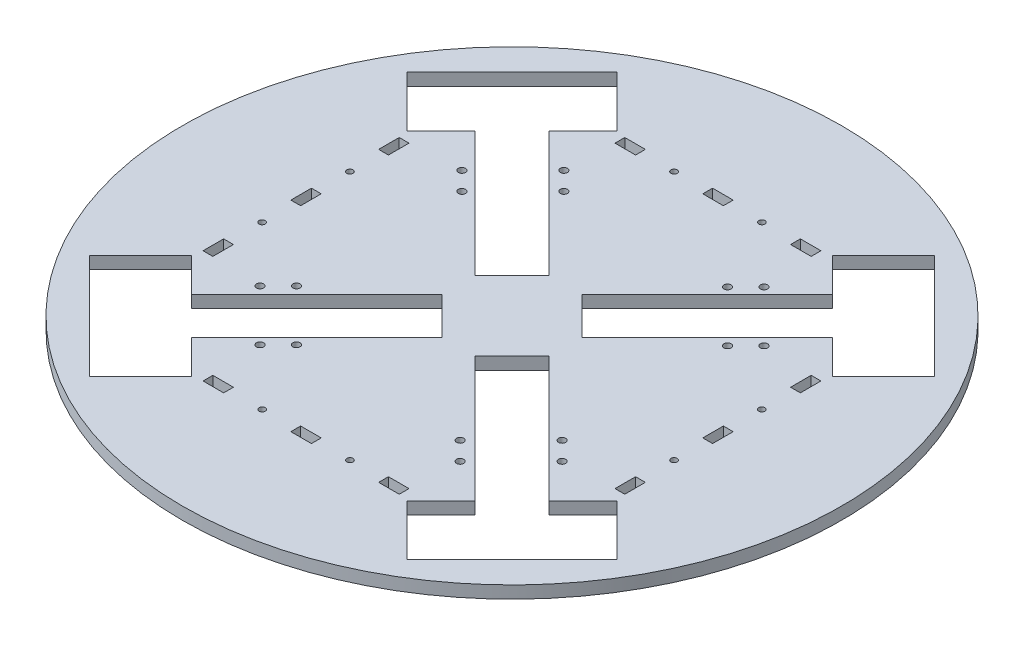
SolidWorks part; units mm, degrees
ref_plane "Front Plane" through (0, 0, 0) normal (0, 0, 1) x (1, 0, 0)
ref_plane "Top Plane" through (0, 0, 0) normal (0, 1, 0) x (1, 0, 0)
ref_plane "Right Plane" through (0, 0, 0) normal (1, 0, 0) x (0, 0, -1)
sketch "Sketch1" plane through (0, 0, 0) normal (0, 1, 0) x (1, 0, 0)
  line L1 (0, 0) -> (-200, 0) construction
  line L2 (0, 0) -> (0, 200) construction
  line L3 (0, 200) -> (-200, 200) construction
  line L4 (-200, 0) -> (-200, 200) construction
  circle A0 centre (-100, 100) radius 160
  point P8 (-100, 200)
  point P9 (-200, 100)
  dimension "D3" = 320
  dimension "D1" = 200
  dimension "D2" = 200
extrude "Boss-Extrude1" add sketch "Sketch1" along normal blind 6 contours A0
sketch "Sketch2" plane through (0, 6, 0) normal (0, 1, 0) x (1, 0, 0)
  line L0 (-260, 100) -> (60, 100) construction
  line L1 (-213.1371, -13.1371) -> (-100, 100) construction
  line L2 (-100, 100) -> (13.1371, 213.1371) construction
  line L3 (-213.1371, 213.1371) -> (13.1371, -13.1371) construction
  circle A0 centre (-100, 100) radius 160 construction
  dimension "D1" = 45
  dimension "D2" = 45
sketch "Sketch3" plane through (0, 0, 0) normal (0, -1, 0) x (1, 0, 0)
  line L0 (-22.9254, -227.9863) -> (-47.6741, -203.2376)
  line L1 (-22.9254, -227.9863) -> (27.9863, -177.0746)
  line L2 (-47.6741, -203.2376) -> (3.2376, -152.3259)
  line L3 (27.9863, -177.0746) -> (3.2376, -152.3259)
  line L4 (3.2376, -47.6741) -> (27.9863, -22.9254)
  line L5 (3.2376, -47.6741) -> (-47.6741, 3.2376)
  line L6 (27.9863, -22.9254) -> (-22.9254, 27.9863)
  line L7 (-47.6741, 3.2376) -> (-22.9254, 27.9863)
  line L8 (-152.3259, 3.2376) -> (-177.0746, 27.9863)
  line L9 (-152.3259, 3.2376) -> (-203.2376, -47.6741)
  line L10 (-177.0746, 27.9863) -> (-227.9863, -22.9254)
  line L11 (-203.2376, -47.6741) -> (-227.9863, -22.9254)
  line L12 (-177.0746, -227.9863) -> (-152.3259, -203.2376)
  line L13 (-177.0746, -227.9863) -> (-227.9863, -177.0746)
  line L14 (-152.3259, -203.2376) -> (-203.2376, -152.3259)
  line L15 (-227.9863, -177.0746) -> (-203.2376, -152.3259)
  line L16 (-213.1371, -213.1371) -> (13.1371, 13.1371) construction
  line L17 (-100, -100) -> (13.1371, -213.1371) construction
  line L18 (-213.1371, 13.1371) -> (-100, -100) construction
  point P26 (2.5305, -202.5305)
  point P27 (2.5305, 2.5305)
  point P28 (-202.5305, 2.5305)
  point P29 (-202.5305, -202.5305)
  dimension "D1" = 35
  dimension "D2" = 15
  dimension "D3" = 15
  dimension "D4" = 15
  dimension "D5" = 15
  dimension "D6" = 72
extrude "Cut-Extrude1" cut sketch "Sketch3" against normal through all
sketch "Sketch4" plane through (0, 0, 0) normal (0, -1, 0) x (1, 0, 0)
  line L0 (-13.2026, -31.2339) -> (-31.2339, -13.2026)
  line L1 (-13.2026, -31.2339) -> (-74.0138, -92.045)
  line L2 (-31.2339, -13.2026) -> (-92.045, -74.0138)
  line L3 (-74.0138, -92.045) -> (-92.045, -74.0138)
  line L4 (-168.7661, -13.2026) -> (-186.7974, -31.2339)
  line L5 (-168.7661, -13.2026) -> (-107.955, -74.0138)
  line L6 (-186.7974, -31.2339) -> (-125.9862, -92.045)
  line L7 (-107.955, -74.0138) -> (-125.9862, -92.045)
  line L8 (-203.2376, -47.6741) -> (-152.3259, 3.2376) construction
  line L9 (-186.7974, -168.7661) -> (-125.9862, -107.955)
  line L10 (-186.7974, -168.7661) -> (-168.7661, -186.7974)
  line L11 (-125.9862, -107.955) -> (-107.955, -125.9862)
  line L12 (-168.7661, -186.7974) -> (-107.955, -125.9862)
  line L13 (-13.2026, -168.7661) -> (-31.2339, -186.7974)
  line L14 (-13.2026, -168.7661) -> (-74.0138, -107.955)
  line L15 (-31.2339, -186.7974) -> (-92.045, -125.9862)
  line L16 (-74.0138, -107.955) -> (-92.045, -125.9862)
  line L17 (-100, -100) -> (13.1371, -213.1371) construction
  line L18 (-213.1371, -213.1371) -> (13.1371, 13.1371) construction
  line L19 (-213.1371, 13.1371) -> (-100, -100) construction
  line L20 (-47.6741, 3.2376) -> (3.2376, -47.6741) construction
  line L21 (-152.3259, -203.2376) -> (-203.2376, -152.3259) construction
  line L22 (3.2376, -152.3259) -> (-47.6741, -203.2376) construction
  point P22 (-83.0294, -116.9706)
  point P23 (-116.9706, -83.0294)
  point P26 (-83.0294, -83.0294)
  point P27 (-116.9706, -116.9706)
  point P35 (-100, -100)
  point P36 (-100, -100)
  line M20 (-203.2376, -152.3259) -> (-152.3259, -203.2376)
  line M22 (-152.3259, 3.2376) -> (-203.2376, -47.6741)
  line M26 (3.2376, -47.6741) -> (-47.6741, 3.2376)
  line M32 (-47.6741, -203.2376) -> (3.2376, -152.3259)
  dimension "D1" = 25.5
  dimension "D2" = 86
extrude "Cut-Extrude2" cut sketch "Sketch4" against normal through all contours L14 L16 L15 M32 | L12 L11 L9 M20 | L7 L5 L6 M22 | L3 L1 L2 M26
sketch "Sketch7" plane through (0, 0, 0) normal (0, -1, 0) x (1, 0, 0)
  line L0 (-152.3259, -203.2376) -> (-168.7661, -186.7974) construction
  line L1 (-168.7661, -186.7974) -> (-107.955, -125.9862) construction
  line L2 (-152.3259, -203.2376) -> (-168.7661, -186.7974) construction
  line L3 (-168.7661, -186.7974) -> (-107.955, -125.9862) construction
  circle A2 centre (-149.0025, -26.673) radius 1.75
  circle A10 centre (-148.5782, -173.7512) radius 1.75
  circle A20 centre (-140.1637, -35.5119) radius 1.75
  circle A21 centre (-164.9124, -60.2606) radius 1.75
  circle A22 centre (-173.7512, -51.4218) radius 1.75
  circle A25 centre (-173.327, -149.0025) radius 1.75
  circle A26 centre (-164.4881, -140.1637) radius 1.75
  circle A27 centre (-139.7394, -164.9124) radius 1.75
  circle A32 centre (-26.673, -50.9975) radius 1.75
  circle A33 centre (-35.5119, -59.8363) radius 1.75
  circle A34 centre (-60.2606, -35.0876) radius 1.75
  circle A35 centre (-51.4218, -26.2488) radius 1.75
  circle A36 centre (-50.9975, -173.327) radius 1.75
  circle A37 centre (-59.8363, -164.4881) radius 1.75
  circle A38 centre (-35.0876, -139.7394) radius 1.75
  circle A39 centre (-26.2488, -148.5782) radius 1.75
  point P29 (-100, -100)
  dimension "D9" = 3.5
  dimension "D1" = 12.5
  dimension "D2" = 35
  dimension "D3" = 35
  dimension "D4" = 12.5
  dimension "D5" = 37.1652
  dimension "D6" = 23.5
  dimension "D7" = 5.05
  dimension "D8" = 29.95
  dimension "D10" = 4
extrude "Cut-Extrude3" cut sketch "Sketch7" against normal through all
sketch "Sketch8" plane through (0, 6, 0) normal (0, 1, 0) x (1, 0, 0)
  line L1 (0, 200) -> (-200, 200) construction
  line L2 (0, 200) -> (0, 0) construction
  line L3 (0, 0) -> (-200, 0) construction
  line L4 (-200, 200) -> (-200, 0) construction
  line L5 (0, 200) -> (-200, 0) construction
  line L6 (0, 0) -> (-200, 200) construction
  point P0 (-100, 100)
  dimension "D1" = 200
  dimension "D2" = 200
sketch "Sketch9" plane through (0, 0, 0) normal (0, -1, 0) x (1, 0, 0)
  line L0 (-2.375, -119.8125) -> (-2.375, -122.8125) construction
  line L1 (-2.375, -122.8125) -> (2.375, -122.8125) construction
  line L2 (2.375, -122.8125) -> (2.375, -119.8125) construction
  line L3 (2.375, -119.8125) -> (-2.375, -119.8125) construction
  line L4 (-2.375, -77.1875) -> (-2.375, -80.1875) construction
  line L5 (-2.375, -80.1875) -> (2.375, -80.1875) construction
  line L6 (2.375, -80.1875) -> (2.375, -77.1875) construction
  line L7 (2.375, -77.1875) -> (-2.375, -77.1875) construction
  line L8 (2.375, -147.625) -> (2.375, -137.625) construction
  line L9 (2.375, -137.625) -> (-2.375, -137.625) construction
  line L10 (-2.375, -137.625) -> (-2.375, -147.625) construction
  line L11 (-2.375, -147.625) -> (2.375, -147.625) construction
  line L12 (2.375, -105) -> (2.375, -95) construction
  line L13 (2.375, -95) -> (-2.375, -95) construction
  line L14 (-2.375, -95) -> (-2.375, -105) construction
  line L15 (-2.375, -105) -> (2.375, -105) construction
  line L16 (2.375, -62.375) -> (2.375, -52.375) construction
  line L17 (2.375, -52.375) -> (-2.375, -52.375) construction
  line L18 (-2.375, -52.375) -> (-2.375, -62.375) construction
  line L19 (-2.375, -62.375) -> (2.375, -62.375) construction
  line L20 (-2.375, -119.8125) -> (-2.375, -122.8125) construction
  line L21 (-2.375, -122.8125) -> (2.375, -122.8125) construction
  line L22 (2.375, -122.8125) -> (2.375, -119.8125) construction
  line L23 (2.375, -119.8125) -> (-2.375, -119.8125) construction
  line L24 (-2.375, -77.1875) -> (-2.375, -80.1875) construction
  line L25 (-2.375, -80.1875) -> (2.375, -80.1875) construction
  line L26 (2.375, -80.1875) -> (2.375, -77.1875) construction
  line L27 (2.375, -77.1875) -> (-2.375, -77.1875) construction
  line L28 (2.375, -147.625) -> (2.375, -137.625)
  line L29 (2.375, -137.625) -> (-2.375, -137.625)
  line L30 (-2.375, -137.625) -> (-2.375, -147.625)
  line L31 (-2.375, -147.625) -> (2.375, -147.625)
  line L32 (2.375, -105) -> (2.375, -95)
  line L33 (2.375, -95) -> (-2.375, -95)
  line L34 (-2.375, -95) -> (-2.375, -105)
  line L35 (-2.375, -105) -> (2.375, -105)
  line L36 (2.375, -62.375) -> (2.375, -52.375)
  line L37 (2.375, -52.375) -> (-2.375, -52.375)
  line L38 (-2.375, -52.375) -> (-2.375, -62.375)
  line L39 (-2.375, -62.375) -> (2.375, -62.375)
  line L40 (-105, -202.375) -> (-95, -202.375)
  line L41 (-95, -202.375) -> (-95, -197.625)
  line L42 (-95, -197.625) -> (-105, -197.625)
  line L43 (-105, -197.625) -> (-105, -202.375)
  line L44 (-62.375, -202.375) -> (-52.375, -202.375)
  line L45 (-52.375, -202.375) -> (-52.375, -197.625)
  line L46 (-52.375, -197.625) -> (-62.375, -197.625)
  line L47 (-62.375, -197.625) -> (-62.375, -202.375)
  line L48 (-147.625, -202.375) -> (-137.625, -202.375)
  line L49 (-137.625, -202.375) -> (-137.625, -197.625)
  line L50 (-137.625, -197.625) -> (-147.625, -197.625)
  line L51 (-147.625, -197.625) -> (-147.625, -202.375)
  line L52 (-202.375, -95) -> (-202.375, -105)
  line L53 (-202.375, -105) -> (-197.625, -105)
  line L54 (-197.625, -105) -> (-197.625, -95)
  line L55 (-197.625, -95) -> (-202.375, -95)
  line L56 (-202.375, -137.625) -> (-202.375, -147.625)
  line L57 (-202.375, -147.625) -> (-197.625, -147.625)
  line L58 (-197.625, -147.625) -> (-197.625, -137.625)
  line L59 (-197.625, -137.625) -> (-202.375, -137.625)
  line L60 (-202.375, -52.375) -> (-202.375, -62.375)
  line L61 (-202.375, -62.375) -> (-197.625, -62.375)
  line L62 (-197.625, -62.375) -> (-197.625, -52.375)
  line L63 (-197.625, -52.375) -> (-202.375, -52.375)
  line L64 (-95, 2.375) -> (-105, 2.375)
  line L65 (-105, 2.375) -> (-105, -2.375)
  line L66 (-105, -2.375) -> (-95, -2.375)
  line L67 (-95, -2.375) -> (-95, 2.375)
  line L68 (-137.625, 2.375) -> (-147.625, 2.375)
  line L69 (-147.625, 2.375) -> (-147.625, -2.375)
  line L70 (-147.625, -2.375) -> (-137.625, -2.375)
  line L71 (-137.625, -2.375) -> (-137.625, 2.375)
  line L72 (-52.375, 2.375) -> (-62.375, 2.375)
  line L73 (-62.375, 2.375) -> (-62.375, -2.375)
  line L74 (-62.375, -2.375) -> (-52.375, -2.375)
  line L75 (-52.375, -2.375) -> (-52.375, 2.375)
  circle A0 centre (0, -78.6875) radius 1.5
  circle A1 centre (0, -121.3125) radius 1.5
  circle A2 centre (-78.6875, -200) radius 1.5
  circle A3 centre (-121.3125, -200) radius 1.5
  circle A4 centre (-200, -121.3125) radius 1.5
  circle A5 centre (-200, -78.6875) radius 1.5
  circle A6 centre (-121.3125, 0) radius 1.5
  circle A7 centre (-78.6875, 0) radius 1.5
  point P12 (2.375, -78.6875)
  point P15 (0, -80.1875)
  point P22 (2.375, -121.3125)
  dimension "D1" = 4
extrude "Cut-Extrude4" cut sketch "Sketch9" against normal through all
